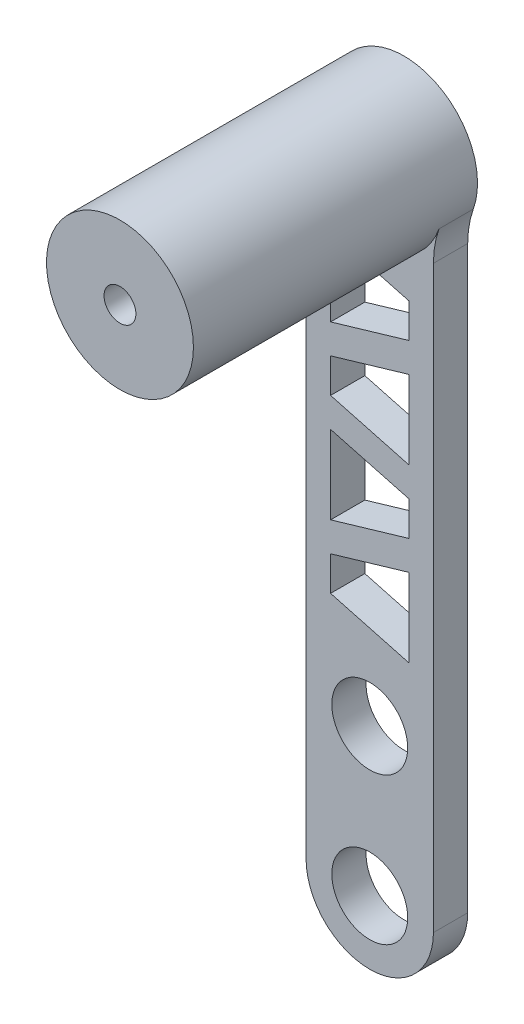
SolidWorks part; units mm, degrees
ref_plane "Front Plane" through (0, 0, 0) normal (0, 0, 1) x (1, 0, 0)
ref_plane "Top Plane" through (0, 0, 0) normal (0, 1, 0) x (1, 0, 0)
ref_plane "Right Plane" through (0, 0, 0) normal (1, 0, 0) x (0, 0, -1)
sketch "Sketch1" plane through (0, 0, 0) normal (0, 0, 1) x (1, 0, 0)
  line L0 (-1.1218, 98.318) -> (-1.1218, -78.4144) construction
  line L1 (-14.1218, 65.8174) -> (-14.1218, -52.5207)
  line L2 (-9.1218, 3.9577) -> (-9.1218, -3.0423)
  line L3 (-9.1218, -3.0423) -> (6.8782, -7.3295)
  line L4 (6.8782, -7.3295) -> (6.8782, 8.6705)
  line L5 (6.8782, 8.6705) -> (-9.1218, 3.9577)
  line L6 (-9.1218, 31.9577) -> (6.8782, 27.6705)
  line L7 (-9.1218, 38.9577) -> (-9.1218, 31.9577)
  line L8 (6.8782, 43.6705) -> (-9.1218, 38.9577)
  line L9 (6.8782, 27.6705) -> (6.8782, 43.6705)
  line L10 (6.8782, 56.6705) -> (-9.1218, 60.9577)
  line L11 (6.8782, 49.6705) -> (6.8782, 56.6705)
  line L12 (-9.1218, 44.9577) -> (6.8782, 49.6705)
  line L13 (-9.1218, 60.9577) -> (-9.1218, 44.9577)
  line L14 (-9.1218, 9.9577) -> (6.8782, 14.6705)
  line L15 (6.8782, 14.6705) -> (6.8782, 21.6705)
  line L16 (6.8782, 21.6705) -> (-9.1218, 25.9577)
  line L17 (-9.1218, 25.9577) -> (-9.1218, 9.9577)
  line L18 (11.8782, 65.8174) -> (11.8782, -52.5207)
  circle A0 centre (-1.1218, -52.5207) radius 7.75
  circle A1 centre (-1.1218, -22.5207) radius 7.75
  circle A2 centre (-1.1218, 77.4793) radius 7.75
  arc A3 (13.0211, 72.4813) -> (-15.2646, 72.4813) centre (-1.1218, 77.4793) ccw
  arc A4 (-14.1218, -52.5207) -> (11.8782, -52.5207) centre (-1.1218, -52.5207) ccw
  arc A5 (11.8782, 65.8174) -> (13.0211, 72.4813) centre (31.8782, 65.8174) cw
  arc A6 (-15.2646, 72.4813) -> (-14.1218, 65.8174) centre (-34.1218, 65.8174) cw
  point P29 (11.8782, 69.996)
  point P33 (-14.1218, 69.996)
  dimension "D1" = 15.5
  dimension "D15" = 30
  dimension "D16" = 20
  dimension "D17" = 20
  dimension "D2" = 30
  dimension "D3" = 100
  dimension "D4" = 13
  dimension "D5" = 5
  dimension "D6" = 7
  dimension "D7" = 16
  dimension "D8" = 75
  dimension "D9" = 16
  dimension "D10" = 2
  dimension "D11" = 6
  dimension "D13" = 6
  dimension "D14" = 6
  dimension "D12" = 2
extrude "Boss-Extrude1" add sketch "Sketch1" along normal blind 7
sketch "Sketch2" plane through (0, 0, 7) normal (0, 0, 1) x (1, 0, 0)
  circle A2 centre (-1.1218, 77.4793) radius 3.25
  circle A3 centre (-1.1218, 77.4793) radius 15
  dimension "D1" = 6.5
extrude "Boss-Extrude2" add sketch "Sketch2" along normal blind 51
